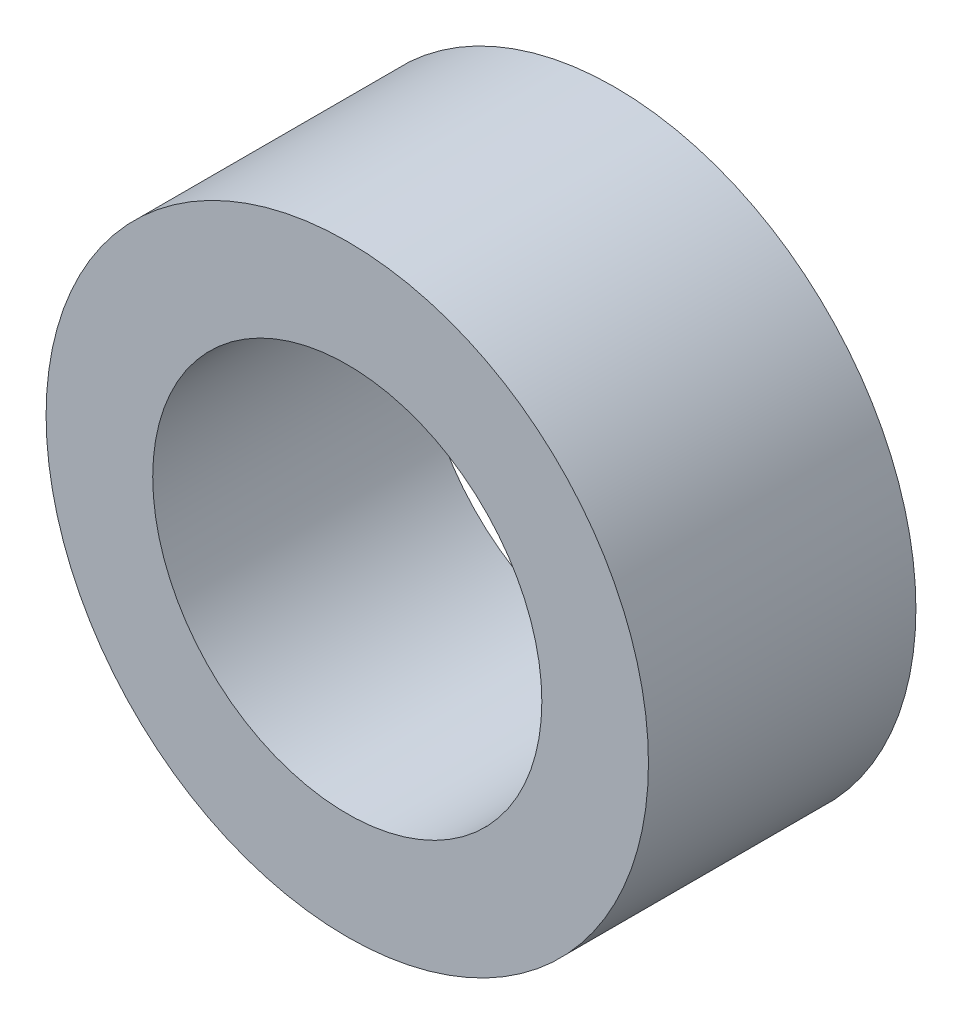
SolidWorks part; units mm, degrees
ref_plane "Front Plane" through (0, 0, 0) normal (0, 0, 1) x (1, 0, 0)
ref_plane "Top Plane" through (0, 0, 0) normal (0, 1, 0) x (1, 0, 0)
ref_plane "Right Plane" through (0, 0, 0) normal (1, 0, 0) x (0, 0, -1)
sketch "Sketch1" plane through (0, 0, 0) normal (0, 0, 1) x (1, 0, 0)
  circle A0 centre (0, 0) radius 4.1021
  circle A1 centre (0, 0) radius 6.35
  dimension "D1" = 12.7
  dimension "D2" = 8.2042
extrude "Boss-Extrude1" add sketch "Sketch1" along normal blind 5.6388
equation "\"OD\"= .5"
equation "\"ID\"= .323"
equation "\"L\" = .222"
equation "\"D1@Sketch1\"=\"OD\""
equation "\"D2@Sketch1\"=\"ID\""
equation "\"D1@Boss-Extrude1\"=\"L\""
